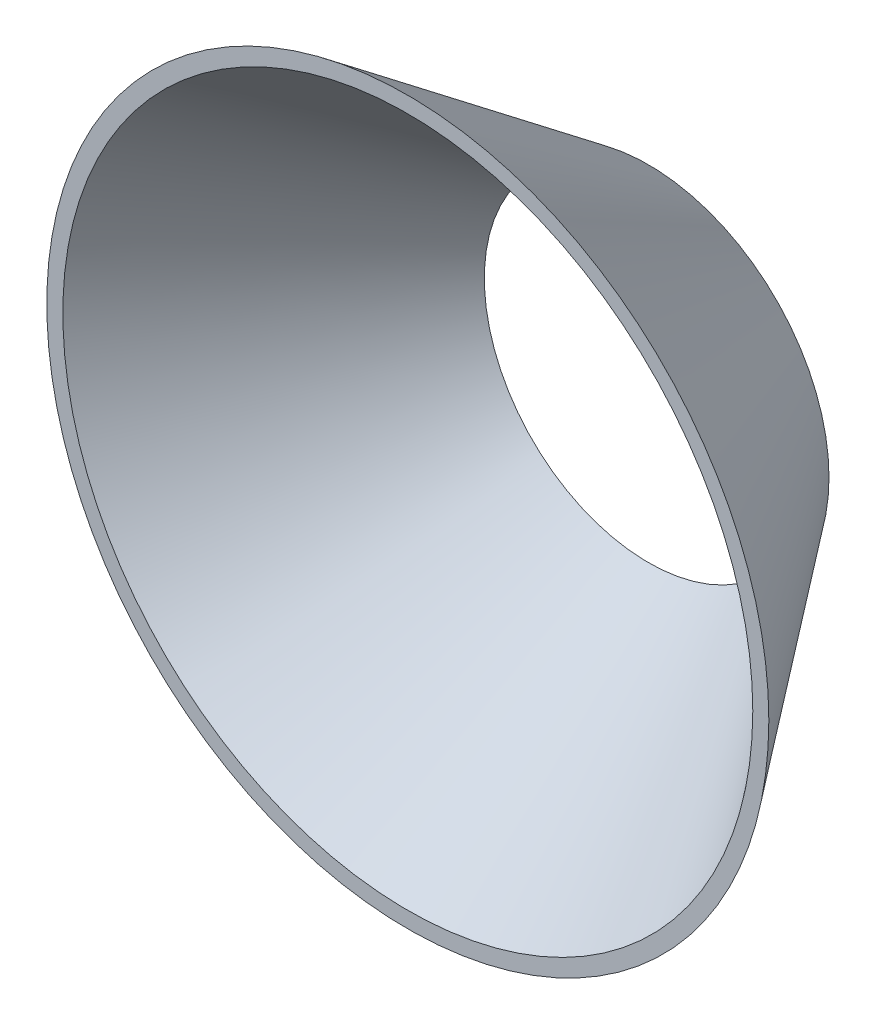
SolidWorks part; units mm, degrees
ref_plane "Front Plane" through (0, 0, 0) normal (0, 0, 1) x (1, 0, 0)
ref_plane "Top Plane" through (0, 0, 0) normal (0, 1, 0) x (1, 0, 0)
ref_plane "Right Plane" through (0, 0, 0) normal (1, 0, 0) x (0, 0, -1)
sketch "Sketch5" plane through (0, 0, 0) normal (0, 1, 0) x (1, 0, 0)
  line L0 (0, 0) -> (0, 60)
  line L1 (0, -55) -> (0, 55) construction
  line L2 (-43, 0) -> (-20.4648, 30)
  line L3 (-55, 0) -> (55, 0) construction
  line L4 (-22.5, 30) -> (-45, 0)
  line L5 (-45, 0) -> (-43, 0)
  line L7 (0, 57.3333) -> (0, 60)
  line L8 (0, 60) -> (-0.2969, 60.1737)
  line L9 (-22.5, 30) -> (-20.4648, 30)
revolve "Revolve2" add sketch "Sketch5" angle 360 about L0
